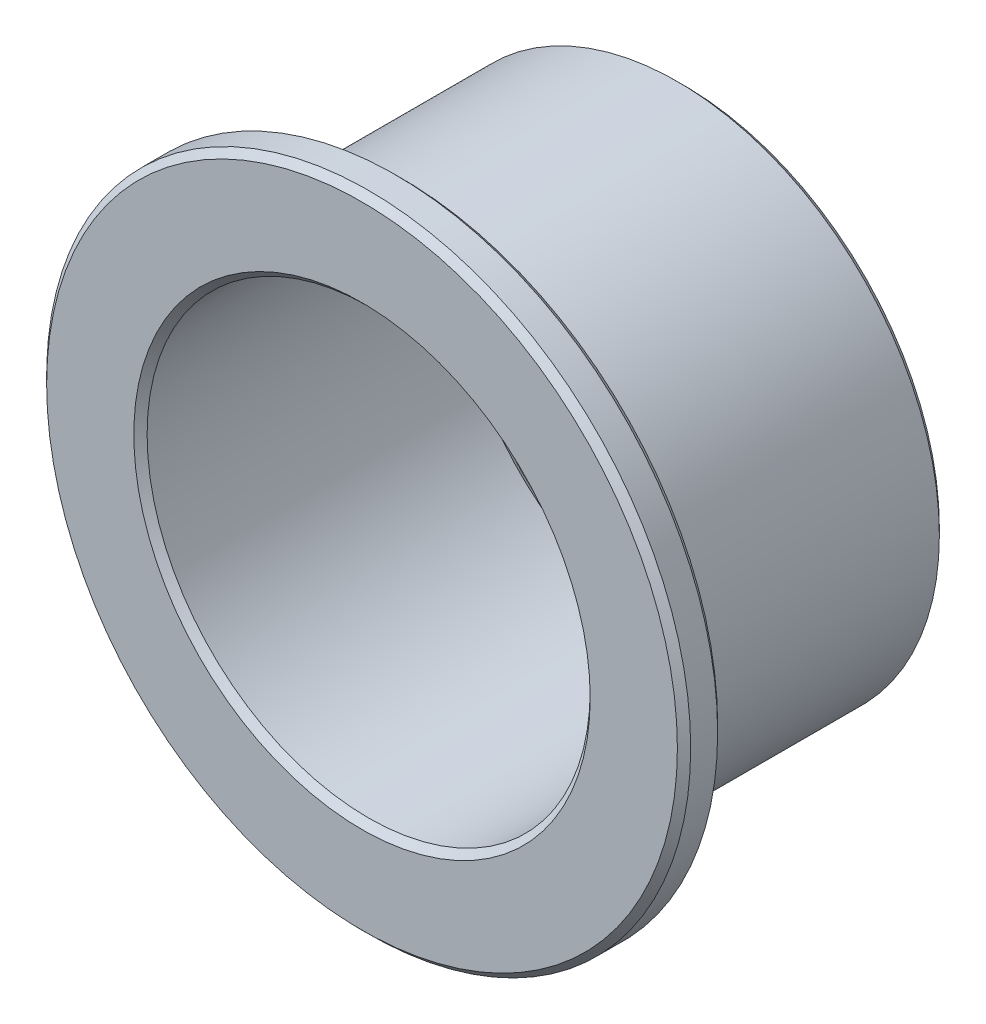
SolidWorks part; units mm, degrees
material "Manganese Bronze"
ref_plane "Front" through (0, 0, 0) normal (0, 0, 1) x (1, 0, 0)
ref_plane "Top" through (0, 0, 0) normal (0, 1, 0) x (1, 0, 0)
ref_plane "Right" through (0, 0, 0) normal (1, 0, 0) x (0, 0, -1)
sketch "Sketch1" plane through (0, 0, 0) normal (0, 0, 1) x (1, 0, 0)
  circle A0 centre (0, 0) radius 17.4752
  circle A1 centre (0, 0) radius 20.6629
  circle A2 centre (0, 0) radius 25.4
  dimension "ID" = 34.9504
  dimension "OD" = 41.3258
  dimension "Flange OD" = 50.8
sketch "Sketch2" plane through (0, 0, 0) normal (1, 0, 0) x (0, 0, -1)
  line L0 (-12.7, -25.4) -> (12.7, -25.4) construction
  line L1 (0, 25.4) -> (0, -25.4) construction
  line L3 (-9.525, 20.6629) -> (12.7, 20.6629) construction
  point P3 (0, -25.4)
  point P7 (0, 20.6629)
  point P9 (-9.525, -25.4)
  point P10 (-12.7, 25.4)
  point P23 (0, 25.4)
  dimension "Flange Thickness" = 3.175
  dimension "Length" = 25.4
sketch "Sketch3" plane through (0, 0, 0) normal (0, 0, 1) x (1, 0, 0)
  circle A0 centre (0, 0) radius 25.4 construction
  circle A1 centre (0, 0) radius 25.4
  circle A2 centre (0, 0) radius 17.4752 construction
  circle A3 centre (0, 0) radius 17.4752
extrude "Boss-Extrude1" add sketch "Sketch3" against normal up to vertex (-9.525 mm away) from vertex at 12.7 starting at point (0, -25.4, 12.7)
sketch "Sketch4" plane through (0, 0, 0) normal (0, 0, 1) x (1, 0, 0)
  circle A0 centre (0, 0) radius 17.4752 construction
  circle A1 centre (0, 0) radius 20.6629 construction
  circle A2 centre (0, 0) radius 17.4752
  circle A3 centre (0, 0) radius 20.6629
extrude "Boss-Extrude2" add sketch "Sketch4" against normal up to vertex (12.7 mm away) from vertex at 9.525 starting at point (0, -25.4, 9.525)
chamfer "Chamfer1" distance 0.5243 angle 45 6 edges at (17.4752, 0, 12.7) (25.4, 0, 12.7) (25.4, 0, 9.525) (20.6629, 0, 9.525) (17.4752, 0, -12.7) (20.6629, 0, -12.7)
equation "\"D1@Chamfer1\"=\"ID@Sketch1\"*0.015"
